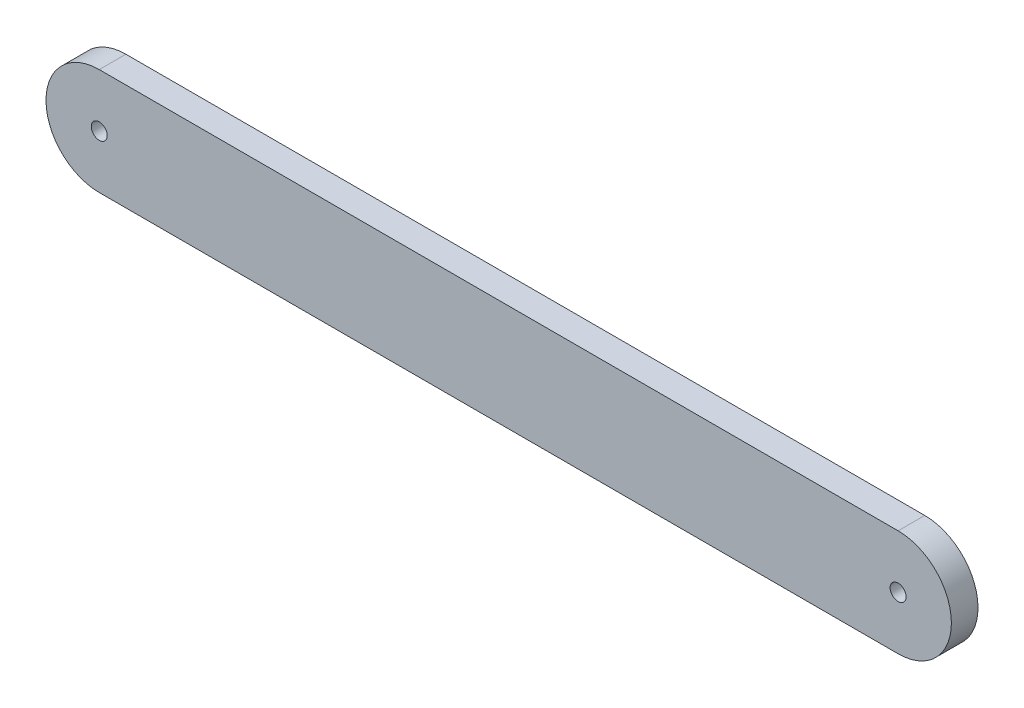
SolidWorks part; units mm, degrees
material "PVC 0.007 Plasticized"
ref_plane "Front Plane" through (0, 0, 0) normal (0, 0, 1) x (1, 0, 0)
ref_plane "Top Plane" through (0, 0, 0) normal (0, 1, 0) x (1, 0, 0)
ref_plane "Right Plane" through (0, 0, 0) normal (1, 0, 0) x (0, 0, -1)
sketch "Sketch1" plane through (0, 0, 0) normal (0, 0, 1) x (1, 0, 0)
  line L0 (-75, 0) -> (75, 0)
  dimension "D1" = 150
  dimension "D2" = 75
sketch "Sketch2" plane through (0, 0, 0) normal (0, 0, 1) x (1, 0, 0)
  line L0 (-75, 10) -> (75, 10)
  line L1 (-75, -10) -> (75, -10)
  arc A0 (-75, 10) -> (-75, -10) centre (-75, 0) ccw
  arc A1 (75, -10) -> (75, 10) centre (75, 0) ccw
  dimension "D1" = 20
  dimension "D2" = 20
extrude "Boss-Extrude1" add sketch "Sketch2" along normal blind 5
sketch "Sketch4" plane through (0, 0, 0) normal (0, 0, -1) x (-1, 0, 0)
  circle A1 centre (-75, 0) radius 1.5
  circle A3 centre (75, 0) radius 1.5
  dimension "D1" = 3
  dimension "D2" = 3
extrude "Cut-Extrude1" cut sketch "Sketch4" against normal blind 5
